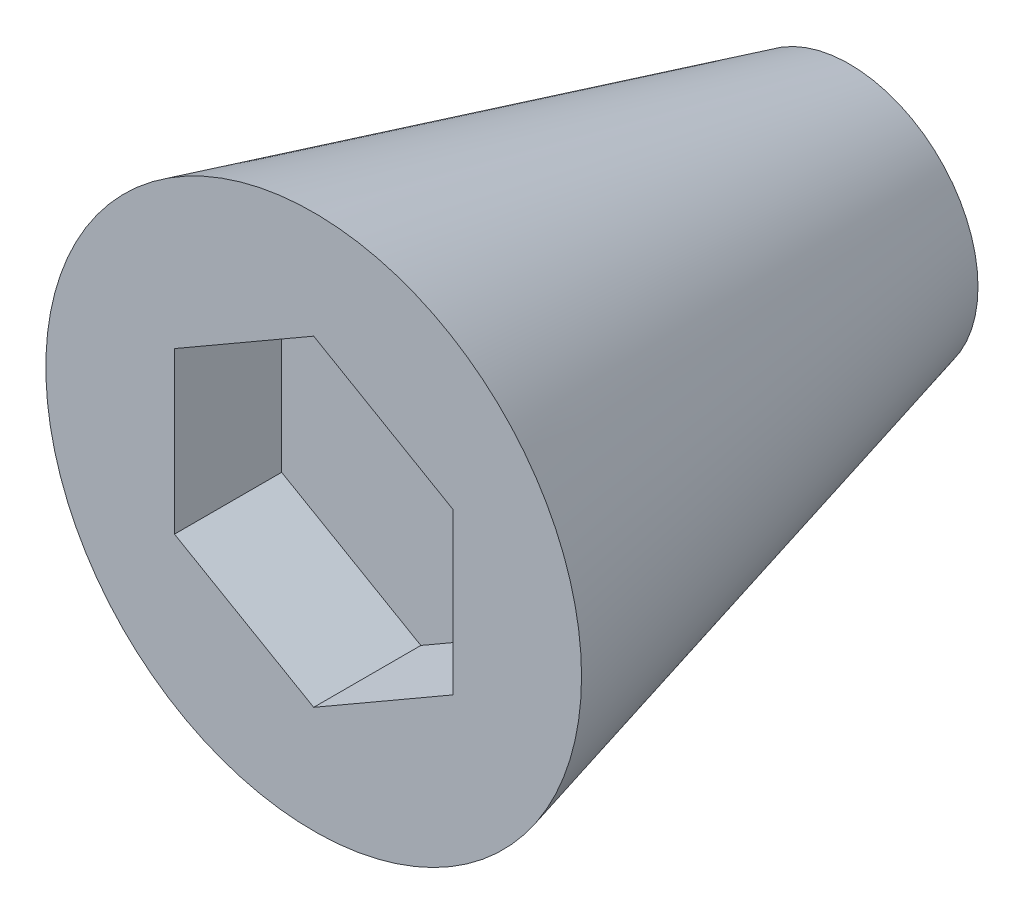
SolidWorks part; units mm, degrees
ref_plane "前视基准面" through (0, 0, 0) normal (0, 0, 1) x (1, 0, 0)
ref_plane "上视基准面" through (0, 0, 0) normal (0, 1, 0) x (1, 0, 0)
ref_plane "右视基准面" through (0, 0, 0) normal (1, 0, 0) x (0, 0, -1)
other "Configuration Table"
sketch "草图1" plane through (0, 0, 0) normal (0, 1, 0) x (1, 0, 0)
  line L0 (0, 0) -> (0, 30.7719) construction
  line L1 (0, 50) -> (12, 50)
  line L2 (12, 50) -> (25, 0)
  line L3 (25, 0) -> (0, 0)
  line L4 (0, 0) -> (0, 50)
  line L5 (0, 20) -> (19.8, 20)
  dimension "D1" = 12
  dimension "D2" = 25
  dimension "D3" = 50
  dimension "D4" = 30
revolve "旋转1" add sketch "草图1" angle 360 about L0
sketch "草图2" plane through (0, 0, -50) normal (0, 0, -1) x (-1, 0, 0)
  line L1 (0, 6.9282) -> (-6, 3.4641)
  line L2 (-6, 3.4641) -> (-6, -3.4641)
  line L3 (-6, -3.4641) -> (0, -6.9282)
  line L4 (0, -6.9282) -> (6, -3.4641)
  line L5 (6, -3.4641) -> (6, 3.4641)
  line L6 (6, 3.4641) -> (0, 6.9282)
  circle A0 centre (0, 0) radius 6 construction
  dimension "D1" = 12
extrude "切除-拉伸1" cut sketch "草图2" against normal blind 5
sketch "草图3" plane through (0, 0, 0) normal (0, 0, 1) x (1, 0, 0)
  line L1 (0, 15) -> (-12.9904, 7.5)
  line L2 (-12.9904, 7.5) -> (-12.9904, -7.5)
  line L3 (-12.9904, -7.5) -> (0, -15)
  line L4 (0, -15) -> (12.9904, -7.5)
  line L5 (12.9904, -7.5) -> (12.9904, 7.5)
  line L6 (12.9904, 7.5) -> (0, 15)
  circle A0 centre (0, 0) radius 12.9904 construction
  dimension "D1" = 30
extrude "切除-拉伸2" cut sketch "草图3" against normal blind 10
